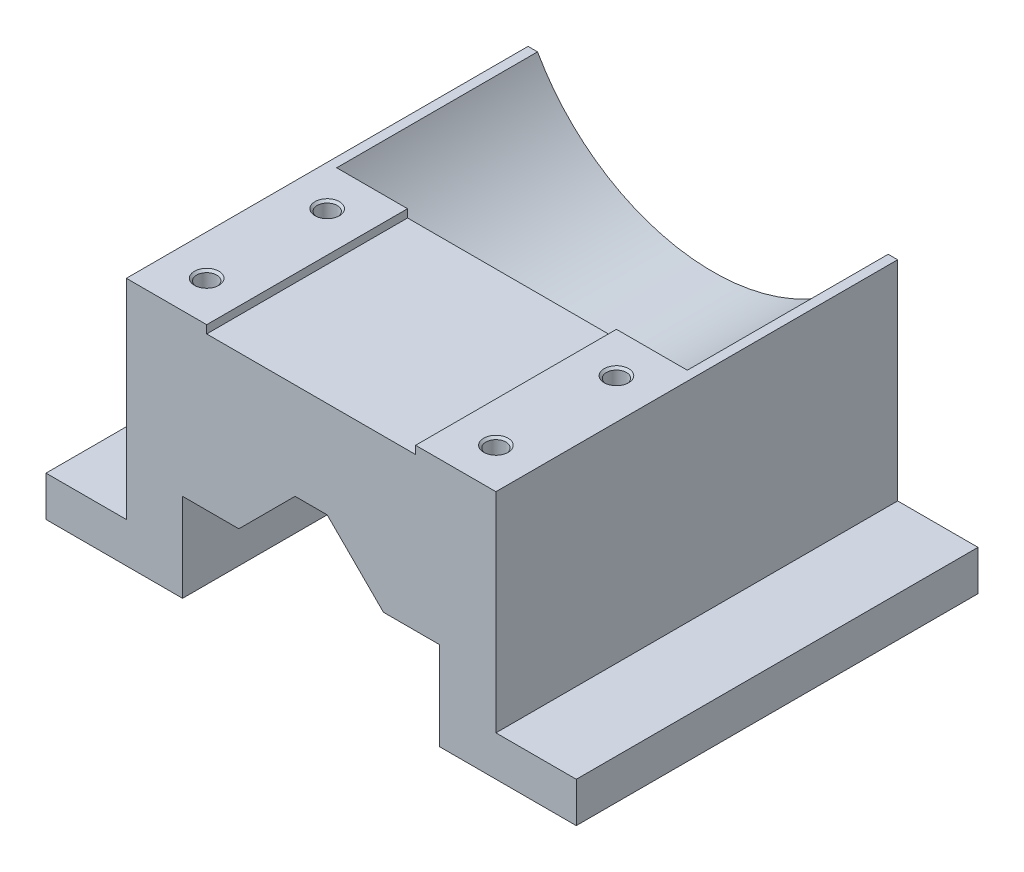
SolidWorks part; units mm, degrees
ref_plane "Front Plane" through (0, 0, 0) normal (0, 0, 1) x (1, 0, 0)
ref_plane "Top Plane" through (0, 0, 0) normal (0, 1, 0) x (1, 0, 0)
ref_plane "Right Plane" through (0, 0, 0) normal (1, 0, 0) x (0, 0, -1)
sketch "Sketch1" plane through (0, 0, 0) normal (0, 0, 1) x (1, 0, 0)
  line L0 (-13, 0) -> (13, 0)
  line L1 (-13, 0) -> (-13, 1)
  line L2 (-13, 1) -> (-23, 1)
  line L3 (-23, 1) -> (-23, -25)
  line L4 (-23, -25) -> (-33, -25)
  line L5 (-33, -25) -> (-33, -30)
  line L6 (-33, -30) -> (-16, -30)
  line L7 (-16, -30) -> (-16, -19)
  line L9 (0, 0) -> (0, -35.9459) construction
  line L10 (-16, -19) -> (-9, -19)
  line L12 (2, -12) -> (-2, -12)
  line L13 (-2, -12) -> (-9, -19)
  line L14 (2, -12) -> (9, -19)
  line L15 (16, -19) -> (9, -19)
  line L16 (16, -30) -> (16, -19)
  line L17 (33, -30) -> (16, -30)
  line L18 (33, -25) -> (33, -30)
  line L19 (23, -25) -> (33, -25)
  line L20 (23, 1) -> (23, -25)
  line L21 (13, 1) -> (23, 1)
  line L22 (13, 0) -> (13, 1)
  point P1 (-15.209, 0.859)
  point P13 (0, 0)
  point P16 (0, -7.0863)
  point P18 (0, -12)
  dimension "D2" = 10
  dimension "D3" = 1
  dimension "D4" = 13
  dimension "D5" = 12
  dimension "D6" = 2
  dimension "D7" = 45
  dimension "D8" = 7
  dimension "D9" = 7
  dimension "D10" = 5
  dimension "D11" = 10
  dimension "D12" = 30
extrude "Boss-Extrude1" add sketch "Sketch1" along normal blind 50
sketch "Sketch2" plane through (0, 0, 0) normal (0, 0, -1) x (-1, 0, 0)
  circle A0 centre (0, 13.2) radius 25
  point P2 (0, 0)
  dimension "D1" = 50
  dimension "D2" = 13.2
extrude "Cut-Extrude1" cut sketch "Sketch2" against normal blind 25
hole_wizard "M3x0.5 Tapped Hole1" positions "Sketch3" profile "Sketch4" tap size "M3x0.5" standard "ANSI Metric"
sketch "Sketch3" plane through (0, 1, 0) normal (0, 1, 0) x (1, 0, 0)
  line L0 (-18, -50) -> (-18, -25) construction
  line L1 (-13, -50) -> (-23, -50) construction
  line L3 (18, -50) -> (18, -30.1775) construction
  line L4 (23, -50) -> (13, -50) construction
  line L6 (-13, -37.5) -> (-23, -37.5) construction
  line L7 (-13, -50) -> (-13, -25) construction
  line L8 (-23, -50) -> (-23, 0) construction
  line L9 (-21.8211, -25) -> (-13, -25) construction
  point P0 (-18, -30)
  point P2 (-18, -45)
  point P4 (18, -30)
  point P6 (18, -45)
  point P32 (0, 0)
  point P35 (0, 0)
  point P36 (0, 0)
  point P37 (21.9656, -65)
  point P38 (0, 0)
  point P39 (18, -50)
  dimension "D1" = 15
  dimension "D2" = 7.5
sketch "Sketch4" plane through (-18, 1, 30) normal (1, 0, 0) x (0, 0, 1)
  line L0 (0, 0) -> (0, 11.7511)
  line L1 (0, 11.7511) -> (1.25, 11)
  line L2 (1.25, 11) -> (1.25, 0.275)
  line L3 (1.25, 0.275) -> (1.525, 0)
  line L5 (1.525, 0) -> (0, 0)
  line L6 (-1.25, 0.275) -> (-1.525, 0) construction
  line L10 (0, 11.7511) -> (-1.25, 11) construction
  line L11 (0, -6.35) -> (0, 107.95) construction
  dimension "Tap Drill Dia." = 2.5
  dimension "Tap Drill Depth" = 11
  dimension "Near C'Sink Dia." = 3.05
  dimension "Near C'Sink Angle" = 90
  dimension "Drill Angle" = 118
cosmetic thread "Hole Thread1" parameters "D1"=9.5, "D2"=3
cosmetic thread "Hole Thread2" parameters "D1"=9.5, "D2"=3
cosmetic thread "Hole Thread3" parameters "D1"=9.5, "D2"=3
cosmetic thread "Hole Thread4" parameters "D1"=9.5, "D2"=3
